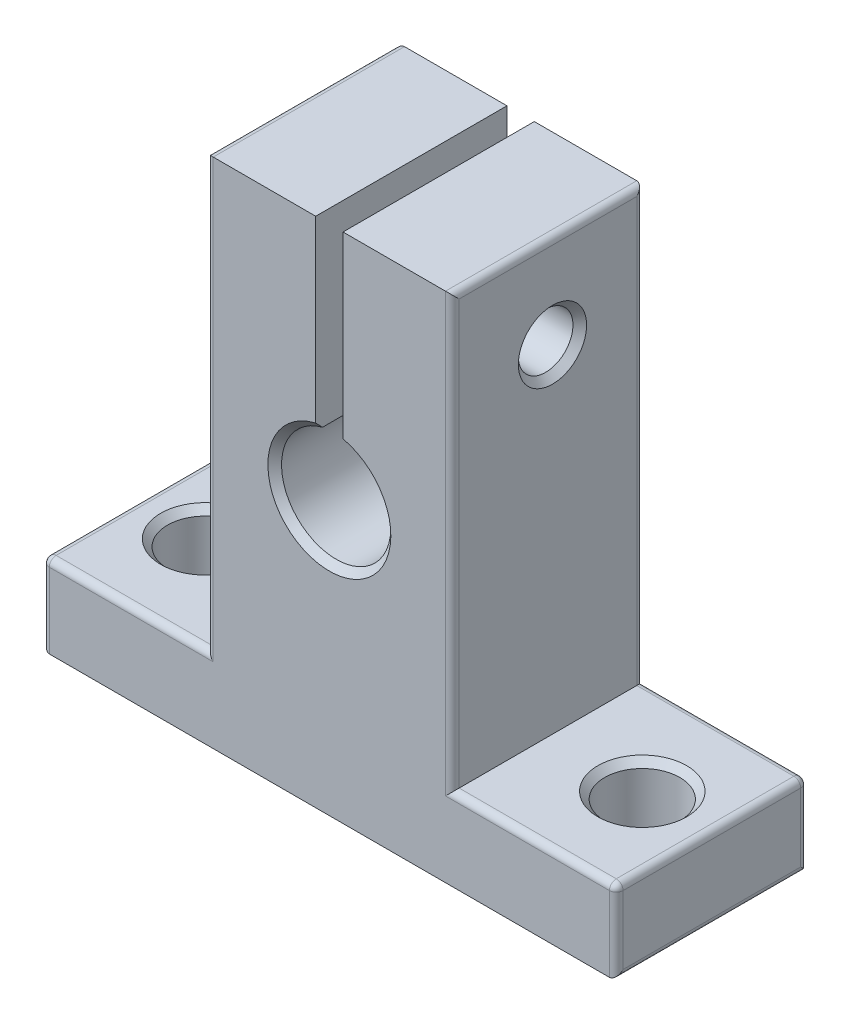
SolidWorks part; units mm, degrees
material "1060 Alloy"
ref_plane "Front Plane" through (0, 0, 0) normal (0, 0, 1) x (1, 0, 0)
ref_plane "Top Plane" through (0, 0, 0) normal (0, 1, 0) x (1, 0, 0)
ref_plane "Right Plane" through (0, 0, 0) normal (1, 0, 0) x (0, 0, -1)
sketch "Sketch1" plane through (0, 0, 0) normal (0, 0, 1) x (1, 0, 0)
  line L0 (0, 0) -> (-50000, 0) construction
  line L1 (0, 0) -> (0, 50000) construction
  line L2 (-21, -3) -> (-21, 3)
  line L3 (-21, 3) -> (-9, 3)
  line L4 (-9, 3) -> (-9, 34.5)
  line L5 (-9, 34.5) -> (-1, 34.5)
  line L6 (9, 34.5) -> (9, 3)
  line L7 (9, 3) -> (21, 3)
  line L8 (21, 3) -> (21, -3)
  line L9 (21, -3) -> (-21, -3)
  line L10 (16, -3) -> (16, 3) construction
  line L11 (-16, -3) -> (-16, 3) construction
  line L12 (-1, 34.5) -> (-1, 20.873)
  line L13 (1, 34.5) -> (1, 20.873)
  line L14 (1, 34.5) -> (9, 34.5)
  arc A0 (-1, 20.873) -> (1, 20.873) centre (0, 17) ccw
  point P8 (-21, 0)
  point P15 (0, -3)
  point P21 (16, 0)
  dimension "Shaft Diameter" = 8
  dimension "W" = 42
  dimension "P" = 18
  dimension "F" = 37.5
  dimension "G" = 6
  dimension "B" = 32
  dimension "D1" = 2
  dimension "h" = 20
extrude "Boss-Extrude1" add sketch "Sketch1" along normal mid plane 14
sketch "Sketch2" plane through (0, 3, 0) normal (0, 1, 0) x (1, 0, 0)
  line L0 (0, 0) -> (50000, 0) construction
  line L1 (0.3141, 0) -> (-49999.6859, 0) construction
  line L2 (-0.0955, 2.4842) -> (-0.0955, 50002.4842) construction
  circle A0 centre (15.9045, 0) radius 2.75
  circle A1 centre (-16.0955, 0) radius 2.75
  dimension "B" = 32
  dimension "S" = 5.5
extrude "Cut-Extrude1" cut sketch "Sketch2" against normal through all
sketch "Sketch5" plane through (-1, 0, 0) normal (1, 0, 0) x (0, 0, -1)
  line L0 (-7, 27.6865) -> (7, 27.6865) construction
  line L1 (7, 20.873) -> (7, 34.5) construction
  line L2 (0, 34.5) -> (0, 20.873) construction
  line L3 (-7, 34.5) -> (7, 34.5) construction
  line L4 (-7, 20.873) -> (7, 20.873) construction
  line L5 (-7, 20.873) -> (-7, 34.5) construction
  circle A0 centre (0.3307, 27.6865) radius 2
  dimension "Clamping bold" = 4
extrude "Cut-Extrude2" cut sketch "Sketch5" against normal through all both and the other way through all
chamfer "Chamfer2" distance 0.5 angle 45 6 edges at (0, 13, -7) (0, 13, 7) (-9, 27.6865, -2.3307) (-13.3455, 3, 0) (9, 27.6865, 1.6693) (13.1545, 3, 0)
fillet "Fillet2" radius 0.5 18 edges at (21, -3, 0) (21, 0, 7) (21, 3, 0) (21, 0, -7) (-21, 3, 0) (-21, 0, 7) (-21, -3, 0) (-21, 0, -7) (-15, 3, -7) (-15, 3, 7) (-9, 18.75, 7) (-9, 34.5, 0) (-9, 18.75, -7) (9, 18.75, -7) (9, 18.75, 7) (15, 3, 7) (15, 3, -7) (9, 34.5, 0)
equation "\"W\"= \"W@Sketch1\"'Width"
equation "\"B\"= \"B@Sketch1\"'between hold"
equation "\"F\"= \"F@Sketch1\"'Hight"
equation "\"P\"= \"P@Sketch1\""
equation "\"G\"= \"G@Sketch1\""
equation "\"Shaft diameter\"= \"Shaft Diameter@Sketch1\""
equation "\"S\"= 5.5'M5"
equation "\"Clamping bold\"= 4'M4"
equation "\"h\"= \"h@Sketch1\""
